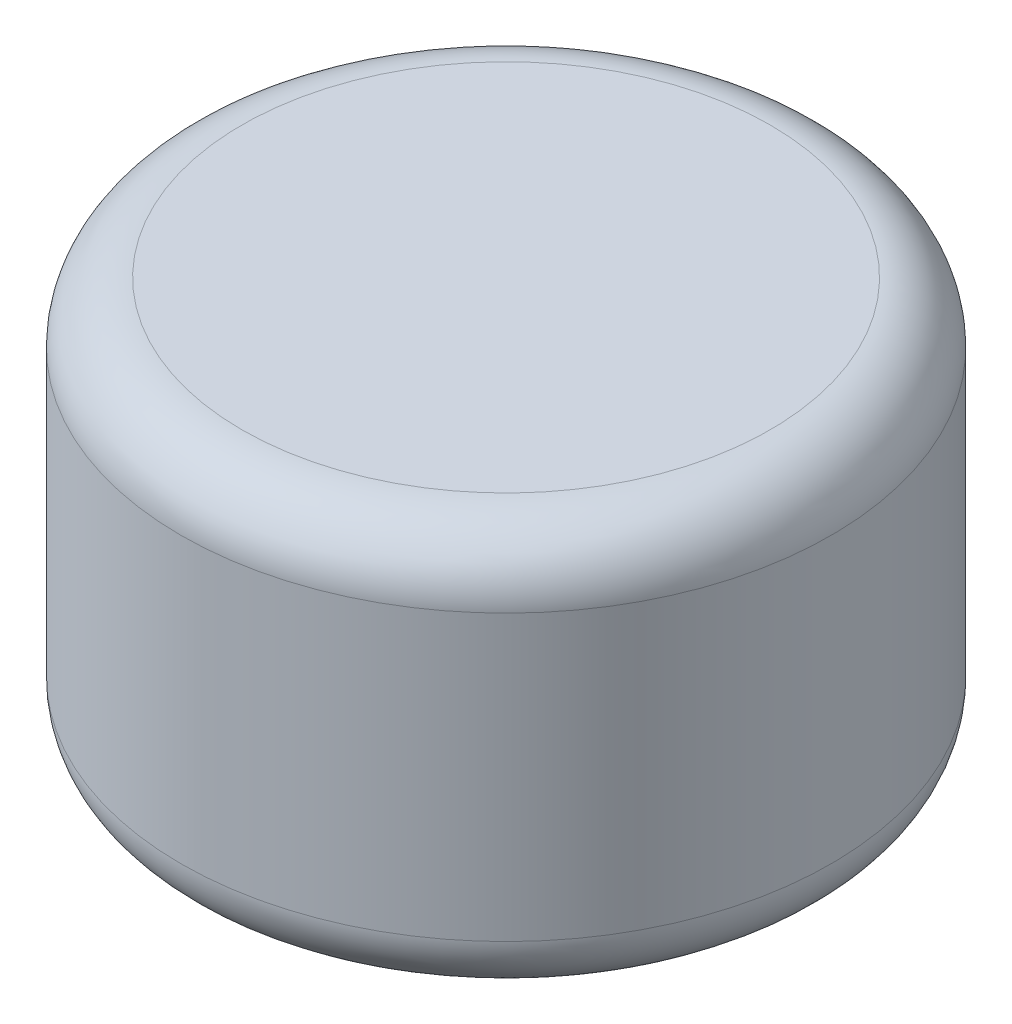
SolidWorks part; units mm, degrees
ref_plane "Front Plane" through (0, 0, 0) normal (0, 0, 1) x (1, 0, 0)
ref_plane "Top Plane" through (0, 0, 0) normal (0, 1, 0) x (1, 0, 0)
ref_plane "Right Plane" through (0, 0, 0) normal (1, 0, 0) x (0, 0, -1)
sketch "Sketch1" plane through (0, 0, 0) normal (0, 1, 0) x (1, 0, 0)
  circle A0 centre (0, 0) radius 16
  dimension "D1" = 32
extrude "Boss-Extrude1" add sketch "Sketch1" along normal blind 20
sketch "Sketch2" plane through (0, 20, 0) normal (0, 1, 0) x (1, 0, 0)
  circle A2 centre (0, 0) radius 14.5
  circle A3 centre (0, 0) radius 14.5
  dimension "D1" = 1.5
extrude "Cut-Extrude1" cut sketch "Sketch2" against normal offset from surface (18 mm away) 2 up to face at (0, 0, 16)
sketch "Sketch3" plane through (0, 20, 0) normal (0, 1, 0) x (1, 0, 0)
  circle A0 centre (0, 0) radius 16 construction
  circle A1 centre (0, 0) radius 16
extrude "Boss-Extrude2" add sketch "Sketch3" against normal blind 2
fillet "Fillet1" radius 5 2 edges at (0, 2, 14.5) (0, 18, 14.5)
fillet "Fillet2" radius 3 2 edges at (0, 0, 16) (0, 20, 16)
